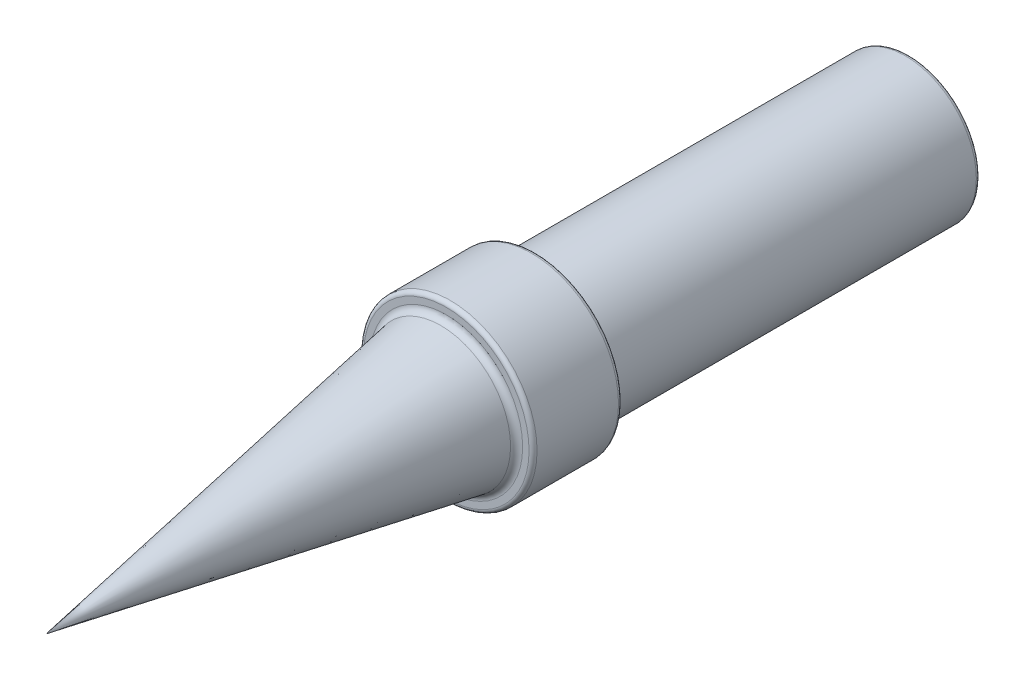
SolidWorks part; units mm, degrees
material "1.4003 (X2CrNi12)"
ref_plane "Plan de face" through (0, 0, 0) normal (0, 0, 1) x (1, 0, 0)
ref_plane "Plan de dessus" through (0, 0, 0) normal (0, 1, 0) x (1, 0, 0)
ref_plane "Plan de droite" through (0, 0, 0) normal (1, 0, 0) x (0, 0, -1)
sketch "Esquisse1" plane through (0, 0, 0) normal (0, 0, 1) x (1, 0, 0)
  circle A0 centre (0, 0) radius 2.65
extrude "Boss.-Extru.1" add sketch "Esquisse1" along normal blind 14
sketch "Esquisse2" plane through (0, 0, 14) normal (0, 0, 1) x (1, 0, 0)
  circle A0 centre (0, 0) radius 3.25
extrude "Boss.-Extru.2" add sketch "Esquisse2" along normal blind 3.35
sketch "Esquisse3" plane through (0, 0, 0) normal (0, 1, 0) x (1, 0, 0)
  line L0 (0, -17.35) -> (0, -32.3402) construction
  line L1 (-3.25, -17.35) -> (3.25, -17.35) construction
  line L2 (0, -32.3402) -> (-2.65, -17.35)
  line L3 (-2.65, -17.35) -> (0, -17.35)
  line L4 (0, -17.35) -> (0, -32.3402)
revolve "Révolution1" add sketch "Esquisse3" angle 360 about L0
fillet "Congé1" radius 0.25 2 edges at (2.65, 0, 14) (2.65, 0, 17.35)
fillet "Congé2" radius 0.15 2 edges at (3.25, 0, 14) (3.25, 0, 17.35)
sketch "Esquisse4" plane through (0, 0, 0) normal (0, 0, -1) x (-1, 0, 0)
  circle A0 centre (0, 0) radius 2.2581
extrude "Enlèv. mat.-Extru.1" cut sketch "Esquisse4" against normal blind 14
fillet "Congé3" radius 0.15 2 edges at (2.65, 0, 0) (-2.2581, 0, 0)
